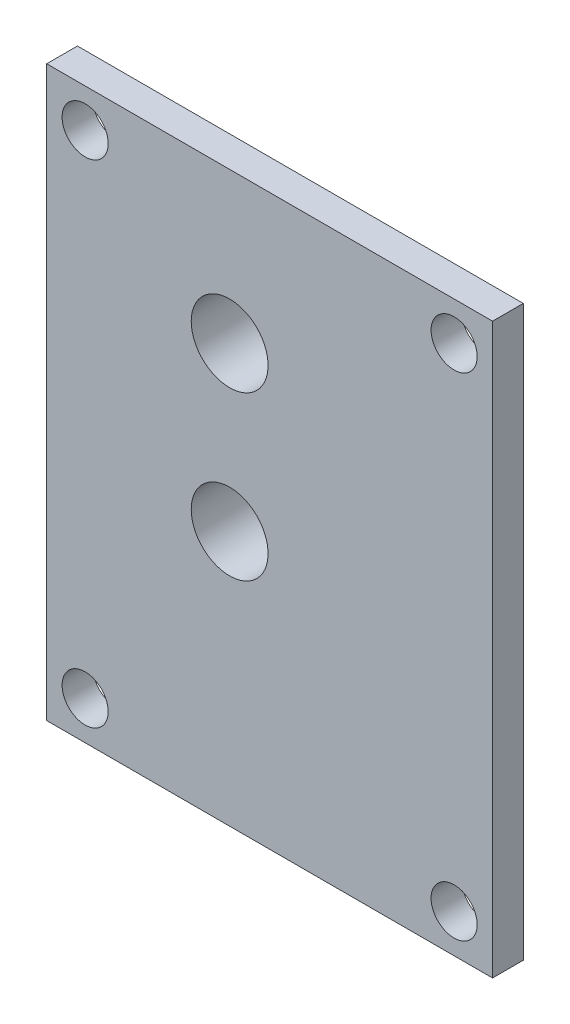
SolidWorks part; units mm, degrees
other "Markup1"
sketch "Sketch1" plane through (75.4275, -12.2708, 2.8126) normal (0.9767, -0.0094, -0.2145) x (0.068, -0.9342, 0.3503)
ref_plane "Front Plane" through (0, 0, 0) normal (0, 0, 1) x (1, 0, 0)
ref_plane "Top Plane" through (0, 0, 0) normal (0, 1, 0) x (1, 0, 0)
ref_plane "Right Plane" through (0, 0, 0) normal (1, 0, 0) x (0, 0, -1)
sketch "Sketch2" plane through (0, 0, 5.6626) normal (0, 0, -1) x (-1, 0, 0)
  line L0 (-57.2725, 16.7442) -> (-75.2725, 16.7442) construction
  line L1 (-75.7725, 17.2442) -> (-56.7725, 17.2442)
  line L2 (-75.7725, 17.2442) -> (-75.7725, -9.7558)
  line L3 (-75.7725, -9.7558) -> (-56.7725, -9.7558)
  line L4 (-56.7725, 17.2442) -> (-56.7725, -9.7558)
  line L5 (-57.2725, -9.2558) -> (-57.2725, 16.7442) construction
  line L6 (-75.2725, 16.7442) -> (-75.2725, -9.2558) construction
  line L7 (-75.2725, -9.2558) -> (-57.2725, -9.2558) construction
  circle A0 centre (-63.6725, 12.4442) radius 2.5
  circle A1 centre (-63.6725, 12.4442) radius 3.5
  circle A2 centre (-63.6725, 1.8442) radius 2.5
  circle A3 centre (-63.6725, 1.8442) radius 3.5
  dimension "D5" = 5
  dimension "D6" = 7
  dimension "D7" = 5
  dimension "D8" = 7
  dimension "D1" = 0.5
  dimension "D2" = 0.5
  dimension "D3" = 0.5
  dimension "D4" = 0.5
extrude "Boss-Extrude1" add sketch "Sketch2" along normal blind 2
sketch "Sketch3" plane through (0, 0, 5.6626) normal (0, 0, -1) x (-1, 0, 0)
  circle A0 centre (-63.6725, 12.4442) radius 2.5
  circle A1 centre (-63.6725, 1.8442) radius 2.5
  circle A2 centre (-63.6725, 12.4442) radius 3.5
  circle A3 centre (-63.6725, 1.8442) radius 3.5
  dimension "D1" = 5
  dimension "D2" = 5
extrude "Boss-Extrude2" add sketch "Sketch3" along normal blind 5
fillet "Fillet1" radius 0.5 2 edges at (60.1725, 1.8442, 0.6626) (60.1725, 12.4442, 0.6626)
sketch "Sketch6" plane through (0, 0, 5.6626) normal (0, 0, 1) x (1, 0, 0)
  line L0 (75.7725, 17.2442) -> (75.7725, -9.7558) construction
  line L1 (80.7725, 22.2442) -> (51.7725, 22.2442)
  line L2 (80.7725, 22.2442) -> (80.7725, -14.7558)
  line L3 (80.7725, -14.7558) -> (51.7725, -14.7558)
  line L4 (51.7725, 22.2442) -> (51.7725, -14.7558)
  line L5 (56.7725, 17.2442) -> (56.7725, -9.7558) construction
  line L6 (75.7725, 17.2442) -> (56.7725, 17.2442) construction
  line L7 (75.7725, -9.7558) -> (56.7725, -9.7558) construction
  line L9 (56.7725, 17.2442) -> (75.7725, 17.2442)
  line L10 (56.7725, 17.2442) -> (56.7725, -9.7558)
  line L11 (56.7725, -9.7558) -> (75.7725, -9.7558)
  line L12 (75.7725, 17.2442) -> (75.7725, -9.7558)
  circle A0 centre (54.2725, 19.7442) radius 1.5
  circle A1 centre (78.2725, 19.7442) radius 1.5
  circle A2 centre (78.2725, -12.2558) radius 1.5
  circle A3 centre (54.2725, -12.2558) radius 1.5
  dimension "D11" = 3
  dimension "D12" = 3
  dimension "D13" = 3
  dimension "D14" = 3
  dimension "D1" = 5
  dimension "D2" = 5
  dimension "D3" = 5
  dimension "D4" = 5
  dimension "D5" = 2.5
  dimension "D6" = 2.5
  dimension "D7" = 2.5
  dimension "D8" = 2.5
  dimension "D9" = 2.5
  dimension "D10" = 2.5
extrude "Boss-Extrude6" add sketch "Sketch6" against normal up to surface (2 mm away) up to face at (60.1725, 1.8442, 3.6626)
